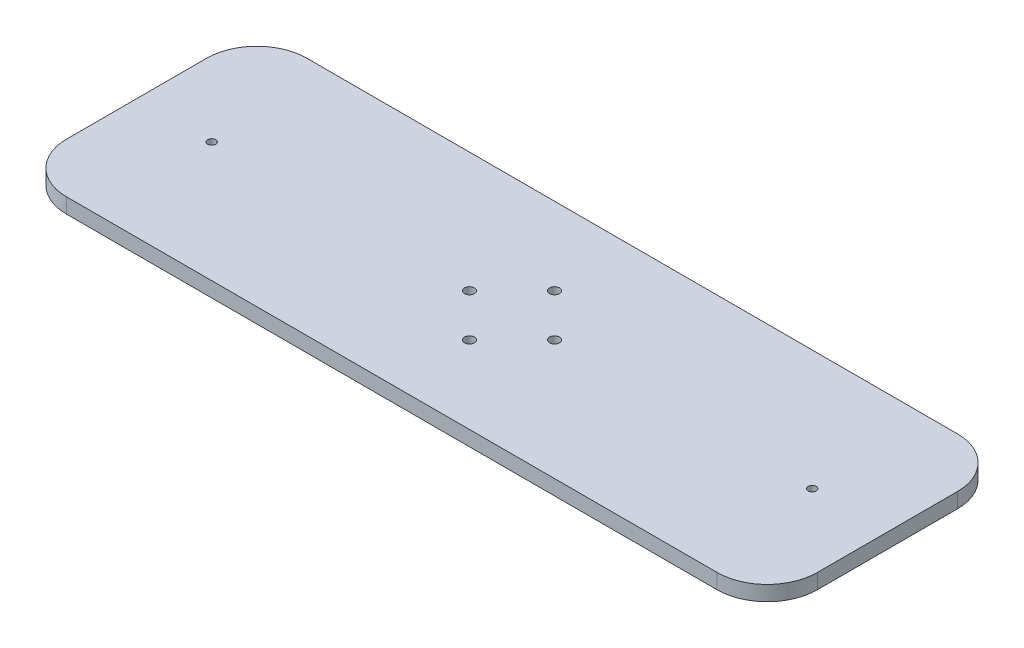
SolidWorks part; units mm, degrees
ref_plane "Front Plane" through (0, 0, 0) normal (0, 0, 1) x (1, 0, 0)
ref_plane "Top Plane" through (0, 0, 0) normal (0, 1, 0) x (1, 0, 0)
ref_plane "Right Plane" through (0, 0, 0) normal (1, 0, 0) x (0, 0, -1)
sketch "Sketch1" plane through (0, 0, 0) normal (0, 1, 0) x (1, 0, 0)
  line L1 (-75, 24) -> (75, 24)
  line L2 (-75, 24) -> (-75, -24)
  line L3 (-75, -24) -> (75, -24)
  line L4 (75, 24) -> (75, -24)
extrude "Boss-Extrude1" add sketch "Sketch1" along normal blind 3
fillet "Fillet1" radius 10 4 edges at (75, 1.5, -24) (75, 1.5, 24) (-75, 1.5, -24) (-75, 1.5, 24)
sketch "Sketch2" plane through (0, 3, 0) normal (0, 1, 0) x (1, 0, 0)
  circle A0 centre (-60, 0) radius 0.8
  circle A1 centre (60, 0) radius 0.8
extrude "Cut-Extrude1" cut sketch "Sketch2" against normal through all
sketch "Sketch3" plane through (0, 3, 0) normal (0, 1, 0) x (1, 0, 0)
  circle A0 centre (-8.5, 0) radius 1
  circle A1 centre (8.5, 0) radius 1
  circle A2 centre (0, 8.5) radius 1
  circle A3 centre (0, -8.5) radius 1
extrude "Cut-Extrude2" cut sketch "Sketch3" against normal through all
